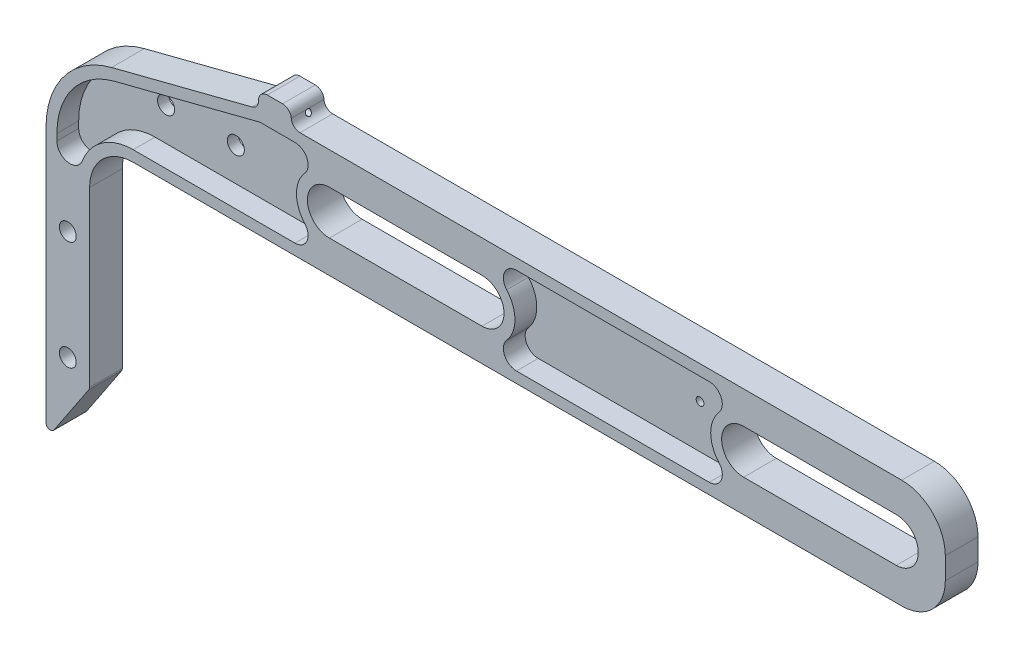
SolidWorks part; units mm, degrees
material "6061-T6 (SS)"
ref_plane "Front Plane" through (0, 0, 0) normal (0, 0, 1) x (1, 0, 0)
ref_plane "Top Plane" through (0, 0, 0) normal (0, 1, 0) x (1, 0, 0)
ref_plane "Right Plane" through (0, 0, 0) normal (1, 0, 0) x (0, 0, -1)
sketch "Sketch1" plane through (0, 0, 0) normal (0, 0, 1) x (1, 0, 0)
  line L0 (-152.4, 79.375) -> (-152.4, 142.875)
  line L1 (-139.7, 139.7) -> (139.7, 139.7) construction
  line L2 (-139.7, 139.7) -> (-139.7, -139.7) construction
  line L3 (-139.7, -139.7) -> (139.7, -139.7) construction
  line L4 (139.7, 139.7) -> (139.7, -139.7) construction
  line L5 (-139.7, 139.7) -> (139.7, -139.7) construction
  line L6 (-139.7, -139.7) -> (139.7, 139.7) construction
  line L7 (-152.4, 142.875) -> (96.8375, 142.875)
  line L8 (96.8375, 142.875) -> (96.8375, 174.625)
  line L9 (96.8375, 174.625) -> (-93.6625, 174.625)
  line L10 (-165.1, 158.75) -> (-165.1, 60.325)
  line L12 (-152.4, 79.375) -> (-165.1, 60.325)
  line L13 (82.55, 158.75) -> (38.1, 158.75) construction
  line L14 (82.55, 152.3365) -> (38.1, 152.3365)
  line L15 (82.55, 165.1635) -> (38.1, 165.1635)
  line L16 (82.55, 158.75) -> (96.8375, 158.75) construction
  line L18 (-82.55, 158.75) -> (-38.1, 158.75) construction
  line L19 (-82.55, 165.1635) -> (-38.1, 165.1635)
  line L20 (-82.55, 152.3365) -> (-38.1, 152.3365)
  line L21 (0, 0) -> (0, 316.08) construction
  line L22 (38.1, 158.75) -> (-38.1, 158.75) construction
  line L23 (-103.1875, 174.625) -> (-103.1875, 179.3875)
  line L24 (-103.1875, 179.3875) -> (-93.6625, 179.3875)
  line L25 (-93.6625, 179.3875) -> (-93.6625, 174.625)
  line L27 (-165.1, 158.75) -> (-103.1875, 174.625)
  arc A0 (82.55, 152.3365) -> (82.55, 165.1635) centre (82.55, 158.75) ccw
  arc A1 (38.1, 165.1635) -> (38.1, 152.3365) centre (38.1, 158.75) ccw
  arc A2 (-82.55, 165.1635) -> (-82.55, 152.3365) centre (-82.55, 158.75) ccw
  arc A3 (-38.1, 152.3365) -> (-38.1, 165.1635) centre (-38.1, 158.75) ccw
  point P0 (0, 0)
  point P10 (60.325, 158.75)
  point P11 (-60.325, 158.75)
  point P33 (0, 158.75)
  dimension "D14" = 4.7625
  dimension "D1" = 279.4
  dimension "D2" = 14.2875
  dimension "D3" = 12.7
  dimension "D4" = 31.75
  dimension "D5" = 63.5
  dimension "D6" = 3.175
  dimension "D7" = 19.05
  dimension "D8" = 15.875
  dimension "D9" = 12.827
  dimension "D10" = 44.45
  dimension "D11" = 190.5
  dimension "D12" = 25.4
  dimension "D13" = 76.2
  dimension "D15" = 9.525
extrude "Boss-Extrude1" add sketch "Sketch1" along normal mid plane 9.525
hole_wizard "#4-40 Tapped Hole1" positions "Sketch26" profile "Sketch28" tap size "#4-40" standard "ANSI Inch" end condition through all
sketch "Sketch26" plane through (0, 0, 4.7625) normal (0, 0, 1) x (1, 0, 0)
  line L0 (19.05, 158.75) -> (38.1, 158.75)
  point P0 (19.05, 158.75)
  dimension "D1" = 19.05
cosmetic thread "Hole Thread5" parameters "D2"=2.8448
sketch "Sketch28" plane through (19.05, 158.75, 4.7625) normal (1, 0, 0) x (0, -1, 0)
  line L0 (0, 0) -> (0, 9.525)
  line L1 (0, 9.525) -> (1.1303, 9.525)
  line L2 (1.1303, 9.525) -> (1.1303, 0)
  line L5 (1.1303, 0) -> (0, 0)
  line L11 (0, -6.35) -> (0, 107.95) construction
  dimension "Thru Tap Drill Dia." = 2.2606
  dimension "Thru Tap Drill Depth" = 9.525
fillet "Fillet1" radius 12.7 2 edges at (96.8375, 142.875, 0) (96.8375, 174.625, 0)
fillet "Fillet2" radius 25.4 1 edges at (-165.1, 158.75, 0)
fillet "Fillet3" radius 12.7 1 edges at (-152.4, 142.875, 0)
sketch "Sketch29" plane through (0, 0, 4.7625) normal (0, 0, 1) x (1, 0, 0)
  line L14 (-100.0125, 172.1614) -> (-145.2201, 160.5697)
  line L15 (-161.925, 139.0411) -> (-161.925, 70.8113)
  line L16 (-161.925, 70.8113) -> (-155.575, 80.3363)
  line L17 (-155.575, 80.3363) -> (-155.575, 130.175)
  line L18 (-139.7, 146.05) -> (84.1375, 146.05)
  line L19 (93.6625, 155.575) -> (93.6625, 161.925)
  line L20 (84.1375, 171.45) -> (-96.8375, 171.45)
  line L21 (-102.7869, 171.45) -> (-145.2201, 160.5697)
  line L22 (-161.925, 139.0411) -> (-161.925, 137.1311)
  line L25 (-139.7, 146.05) -> (-92.5744, 146.05)
  line L27 (28.0756, 171.45) -> (-28.0756, 171.45)
  line L51 (-82.55, 149.1615) -> (-38.1, 149.1615)
  line L52 (-38.1, 168.3385) -> (-82.55, 168.3385)
  line L58 (-92.5744, 171.45) -> (-102.7869, 171.45)
  line L59 (-28.0756, 146.05) -> (28.0756, 146.05)
  line L60 (38.1, 149.1615) -> (82.55, 149.1615)
  line L61 (82.55, 168.3385) -> (38.1, 168.3385)
  line L74 (-96.8375, 171.45) -> (-96.8375, 176.2125)
  line L76 (-96.8375, 176.2125) -> (-100.0125, 176.2125)
  line L78 (-100.0125, 176.2125) -> (-100.0125, 172.1614)
  arc A8 (-145.2201, 160.5697) -> (-161.925, 139.0411) centre (-139.7, 139.0411) ccw
  arc A9 (-139.7, 146.05) -> (-155.575, 130.175) centre (-139.7, 130.175) ccw
  arc A10 (84.1375, 146.05) -> (93.6625, 155.575) centre (84.1375, 155.575) ccw
  arc A11 (93.6625, 161.925) -> (84.1375, 171.45) centre (84.1375, 161.925) ccw
  arc A12 (-145.2201, 160.5697) -> (-161.925, 139.0411) centre (-139.7, 139.0411) ccw
  arc A13 (-139.7, 146.05) -> (-154.5508, 135.7847) centre (-139.7, 130.175) ccw
  arc A44 (-38.1, 149.1615) -> (-38.1, 168.3385) centre (-38.1, 158.75) ccw
  arc A45 (-82.55, 168.3385) -> (-82.55, 149.1615) centre (-82.55, 158.75) ccw
  arc A46 (-30.9262, 152.388) -> (-30.9262, 165.112) centre (-38.1, 158.75) ccw
  arc A47 (-89.7238, 165.112) -> (-89.7238, 152.388) centre (-82.55, 158.75) ccw
  circle A51 centre (19.05, 158.75) radius 4.7625
  arc A52 (30.9262, 165.112) -> (28.0756, 171.45) centre (28.0756, 167.64) ccw
  arc A53 (82.55, 149.1615) -> (82.55, 168.3385) centre (82.55, 158.75) ccw
  arc A54 (38.1, 168.3385) -> (38.1, 149.1615) centre (38.1, 158.75) ccw
  arc A56 (30.9262, 165.112) -> (30.9262, 152.388) centre (38.1, 158.75) ccw
  arc A57 (28.0756, 146.05) -> (30.9262, 152.388) centre (28.0756, 149.86) ccw
  arc A58 (-28.0756, 171.45) -> (-30.9262, 165.112) centre (-28.0756, 167.64) ccw
  arc A59 (-30.9262, 152.388) -> (-28.0756, 146.05) centre (-28.0756, 149.86) ccw
  arc A60 (-89.7238, 165.112) -> (-92.5744, 171.45) centre (-92.5744, 167.64) ccw
  arc A61 (-92.5744, 146.05) -> (-89.7238, 152.388) centre (-92.5744, 149.86) ccw
  arc A62 (-161.925, 137.1311) -> (-154.5508, 135.7847) centre (-158.115, 137.1311) ccw
  dimension "D4" = 9.525
  dimension "D5" = 7.62
  dimension "D1" = 3.175
  dimension "D2" = 3.175
  dimension "D3" = 3.175
extrude "Cut-Extrude1" cut sketch "Sketch29" against normal offset from surface (6.35 mm away) 3.175 contours L21 A12 L22 A62 A13 L25 A61 A47 A60 L58 | L27 A58 A46 A59 L59 A57 A56 A52 up to face at (20.1803, 158.75, -4.7625)
hole_wizard "#10 (0.1935) Diameter Hole1" positions "Sketch30" profile "Sketch31" hole size "#10" standard "ANSI Inch" end condition through all
sketch "Sketch30" plane through (0, 0, 4.7625) normal (0, 0, 1) x (1, 0, 0)
  line L0 (-158.75, 115.8875) -> (-158.75, 84.1375) construction
  line L2 (-165.1, 115.8875) -> (-158.75, 115.8875) construction
  line L6 (-158.75, 115.8875) -> (-152.4, 115.8875) construction
  line L7 (-152.4, 79.375) -> (-152.4, 130.175) construction
  line L9 (-158.75, 115.8875) -> (-165.1, 115.8875)
  line L10 (-139.7, 142.875) -> (84.1375, 142.875) construction
  line L12 (-105.665, 133.35) -> (10.667, 133.35) construction
  line L17 (-165.1, 139.0411) -> (-165.1, 60.325) construction
  line L18 (-165.1, 127) -> (-63.5, 127) construction
  line L20 (-165.1, 120.65) -> (-63.5, 120.65) construction
  line L22 (-152.4, 79.375) -> (-165.1, 79.375) construction
  point P0 (-158.75, 84.1375)
  point P2 (-158.75, 115.8875)
  dimension "D1" = 31.75
  dimension "D2" = 101.6
  dimension "D3" = 9.525
  dimension "D4" = 6.35
  dimension "D5" = 116.332
  dimension "D6" = 101.6
  dimension "D7" = 6.35
  dimension "D8" = 4.7625
sketch "Sketch31" plane through (-158.75, 84.1375, 4.7625) normal (1, 0, 0) x (0, -1, 0)
  line L0 (0, 0) -> (0, 9.525)
  line L1 (0, 9.525) -> (2.4574, 9.525)
  line L2 (2.4574, 9.525) -> (2.4574, 0)
  line L5 (2.4574, 0) -> (0, 0)
  line L11 (0, -6.35) -> (0, 107.95) construction
  dimension "Thru Hole Dia." = 4.9149
  dimension "Thru Hole Depth" = 9.525
fillet "Fillet4" radius 2.54 2 edges at (-103.1875, 174.625, 0) (-93.6625, 174.625, 0)
fillet "Fillet5" radius 2.54 2 edges at (-93.6625, 179.3875, 0) (-103.1875, 179.3875, 0)
sketch "Sketch33" plane through (-103.1875, 0, 0) normal (-1, 0, 0) x (0, 0, 1)
  line L0 (-4.7625, 176.2125) -> (4.7625, 176.2125) construction
  line L1 (4.7625, 176.8475) -> (-4.7625, 176.8475) construction
  line L2 (-4.7625, 176.8475) -> (-4.7625, 176.5959) construction
  line L6 (0, 176.2125) -> (0, 179.5145) construction
  circle A0 centre (0, 176.2125) radius 0.7937
  point P10 (0, 176.2125)
  dimension "D1" = 1.5875
  dimension "D2" = 3.302
  dimension "D3" = 9.525
  dimension "D4" = 0.635
extrude "Cut-Extrude3" cut sketch "Sketch33" against normal through all both and the other way through all
fillet "Fillet6" radius 1.27 2 edges at (-152.4, 79.375, 0) (-165.1, 60.325, 0)
sketch "Sketch34" plane through (0, 0, 4.7625) normal (0, 0, 1) x (1, 0, 0)
  line L1 (112.8791, 174.625) -> (144.9618, 174.625)
  line L2 (112.8791, 174.625) -> (112.8791, 145.4092)
  line L3 (112.8791, 145.4092) -> (144.9618, 145.4092)
  line L4 (144.9618, 174.625) -> (144.9618, 145.4092)
  line L5 (112.8791, 174.625) -> (144.9618, 145.4092) construction
  line L6 (112.8791, 145.4092) -> (144.9618, 174.625) construction
  point P4 (128.9204, 160.0171)
extrude "Boss-Extrude2" [suppressed] add sketch "Sketch34" against normal up to surface (9.525 mm away) separate body
sketch "Sketch35" plane through (0, 0, -4.7625) normal (0, 0, -1) x (-1, 0, 0)
  line L0 (165.1, 105.7402) -> (165.1, 90.5002)
  line L1 (165.1, 105.7402) -> (180.764, 105.7402)
  line L2 (165.1, 90.5002) -> (180.764, 90.5002)
  line L3 (180.764, 105.7402) -> (180.764, 90.5002)
  line L4 (165.1, 139.0411) -> (165.1, 64.5195) construction
  line L5 (152.4, 124.6541) -> (152.4, 109.4141)
  line L6 (152.4, 124.6541) -> (140.7932, 124.6541)
  line L7 (152.4, 109.4141) -> (140.7932, 109.4141)
  line L8 (140.7932, 124.6541) -> (140.7932, 109.4141)
  line L9 (152.4, 79.7595) -> (152.4, 130.175) construction
  line L10 (104.5648, 142.875) -> (89.3248, 142.875)
  line L11 (104.5648, 142.875) -> (104.5648, 130.5539)
  line L12 (89.3248, 142.875) -> (89.3248, 130.5539)
  line L13 (104.5648, 130.5539) -> (89.3248, 130.5539)
  line L14 (139.7, 142.875) -> (-84.1375, 142.875) construction
  line L15 (142.3456, 164.5845) -> (127.5832, 168.3697)
  line L16 (142.3456, 164.5845) -> (145.6066, 177.3024)
  line L17 (127.5832, 168.3697) -> (130.8442, 181.0877)
  line L18 (145.6066, 177.3024) -> (130.8442, 181.0877)
  line L19 (105.0966, 174.1355) -> (146.0087, 163.6452) construction
  line L20 (-65.3921, 174.625) -> (-80.6321, 174.625)
  line L21 (-65.3921, 174.625) -> (-65.3921, 189.8755)
  line L22 (-80.6321, 174.625) -> (-80.6321, 189.8755)
  line L23 (-65.3921, 189.8755) -> (-80.6321, 189.8755)
  line L24 (-84.1375, 174.625) -> (91.1225, 174.625) construction
  line L25 (-54.1655, 142.875) -> (-69.4055, 142.875)
  line L26 (-54.1655, 142.875) -> (-54.1655, 133.0917)
  line L27 (-69.4055, 142.875) -> (-69.4055, 133.0917)
  line L28 (-54.1655, 133.0917) -> (-69.4055, 133.0917)
  line L29 (16.8905, 142.875) -> (1.6505, 142.875)
  line L30 (16.8905, 142.875) -> (16.8905, 131.5167)
  line L31 (1.6505, 142.875) -> (1.6505, 131.5167)
  line L32 (16.8905, 131.5167) -> (1.6505, 131.5167)
  line L33 (56.1063, 174.625) -> (40.8663, 174.625)
  line L34 (56.1063, 174.625) -> (56.1063, 188.9238)
  line L35 (40.8663, 174.625) -> (40.8663, 188.9238)
  line L36 (56.1063, 188.9238) -> (40.8663, 188.9238)
  dimension "D1" = 15.24
extrude "Boss-Extrude3" [suppressed] add sketch "Sketch35" against normal blind 1.27
sketch "Sketch36" [suppressed] plane through (0, 0, 4.7625) normal (0, 0, 1) x (1, 0, 0)
  line L0 (-158.75, 84.1375) -> (-158.75, 129.2444) construction
  circle A0 centre (-158.75, 129.2444) radius 2.4892
  arc A3 (-161.925, 137.1311) -> (-154.5508, 135.7847) centre (-158.115, 137.1311) ccw construction
  circle A4 centre (-158.75, 103.8444) radius 2.4892
  dimension "D1" = 4.9784
  dimension "D2" = 1.5875
  dimension "D3" = 25.4
extrude "Cut-Extrude4" [suppressed] cut sketch "Sketch36" against normal through all
sketch "Sketch38" [suppressed] plane through (0, 0, 4.7625) normal (0, 0, 1) x (1, 0, 0)
  line L4 (-165.1, 60.325) -> (-152.4, 79.375)
  line L5 (-162.7733, 63.8151) -> (-152.6133, 79.0551) construction
  line L7 (-165.1, 100.1782) -> (-165.1, 60.325)
  line L8 (-165.1, 139.0411) -> (-165.1, 64.5195) construction
  line L9 (-152.4, 79.375) -> (-152.4, 100.1782)
  line L10 (-152.4, 79.7595) -> (-152.4, 130.175) construction
  arc A2 (-165.1, 100.1782) -> (-152.4, 100.1782) centre (-158.75, 103.8444) ccw
  dimension "D1" = 14.6647
extrude "Cut-Extrude6" [suppressed] cut sketch "Sketch38" against normal through all
fillet "Fillet7" [suppressed] radius 2.54
sketch "Sketch39" [suppressed] plane through (0, 0, 4.7625) normal (0, 0, 1) x (1, 0, 0)
  line L0 (-82.55, 158.75) -> (-33.3375, 158.75) construction
  line L1 (-82.55, 165.1635) -> (-33.3375, 165.1635)
  line L2 (-82.55, 152.3365) -> (-33.3375, 152.3365)
  line L3 (-38.1, 165.1635) -> (-82.55, 165.1635) construction
  line L5 (38.1, 158.75) -> (87.3125, 158.75) construction
  line L6 (38.1, 165.1635) -> (87.3125, 165.1635)
  line L7 (38.1, 152.3365) -> (87.3125, 152.3365)
  line L8 (38.1, 152.3365) -> (82.55, 152.3365) construction
  arc A0 (-82.55, 165.1635) -> (-82.55, 152.3365) centre (-82.55, 158.75) ccw
  arc A1 (-33.3375, 152.3365) -> (-33.3375, 165.1635) centre (-33.3375, 158.75) ccw
  arc A7 (-82.55, 165.1635) -> (-82.55, 152.3365) centre (-82.55, 158.75) ccw construction
  arc A8 (38.1, 165.1635) -> (38.1, 152.3365) centre (38.1, 158.75) ccw
  arc A9 (87.3125, 152.3365) -> (87.3125, 165.1635) centre (87.3125, 158.75) ccw
  arc A17 (38.1, 165.1635) -> (38.1, 152.3365) centre (38.1, 158.75) ccw construction
  point P2 (-57.9437, 158.75)
  point P15 (62.7063, 158.75)
  dimension "D1" = 6.4135
  dimension "D3" = 6.4135
  dimension "D2" = 49.2125
  dimension "D4" = 49.2125
extrude "Cut-Extrude7" [suppressed] cut sketch "Sketch39" against normal through all both and the other way through all
sketch "Sketch40" plane through (0, 0, 4.7625) normal (0, 0, 1) x (1, 0, 0)
  line L0 (-126.3201, 142.875) -> (-126.3201, 155.784) construction
  line L1 (-144.7733, 142.875) -> (-107.8669, 142.875) construction
  line L2 (-144.7733, 142.875) -> (-144.7733, 198.1892) construction
  line L3 (-144.7733, 198.1892) -> (-107.8669, 198.1892) construction
  line L4 (-107.8669, 142.875) -> (-107.8669, 198.1892) construction
  line L5 (-136.4801, 155.784) -> (-116.1601, 155.784) construction
  line L6 (-139.7, 142.875) -> (84.1375, 142.875) construction
  circle A0 centre (-136.4801, 155.784) radius 2.4892
  circle A1 centre (-116.1601, 155.784) radius 2.4892
  dimension "D3" = 4.9784
  dimension "D1" = 36.9063
  dimension "D2" = 55.3142
  dimension "D4" = 20.32
  dimension "D5" = 12.909
  dimension "D6" = 2.7703
extrude "Cut-Extrude8" cut sketch "Sketch40" against normal through all both and the other way through all
